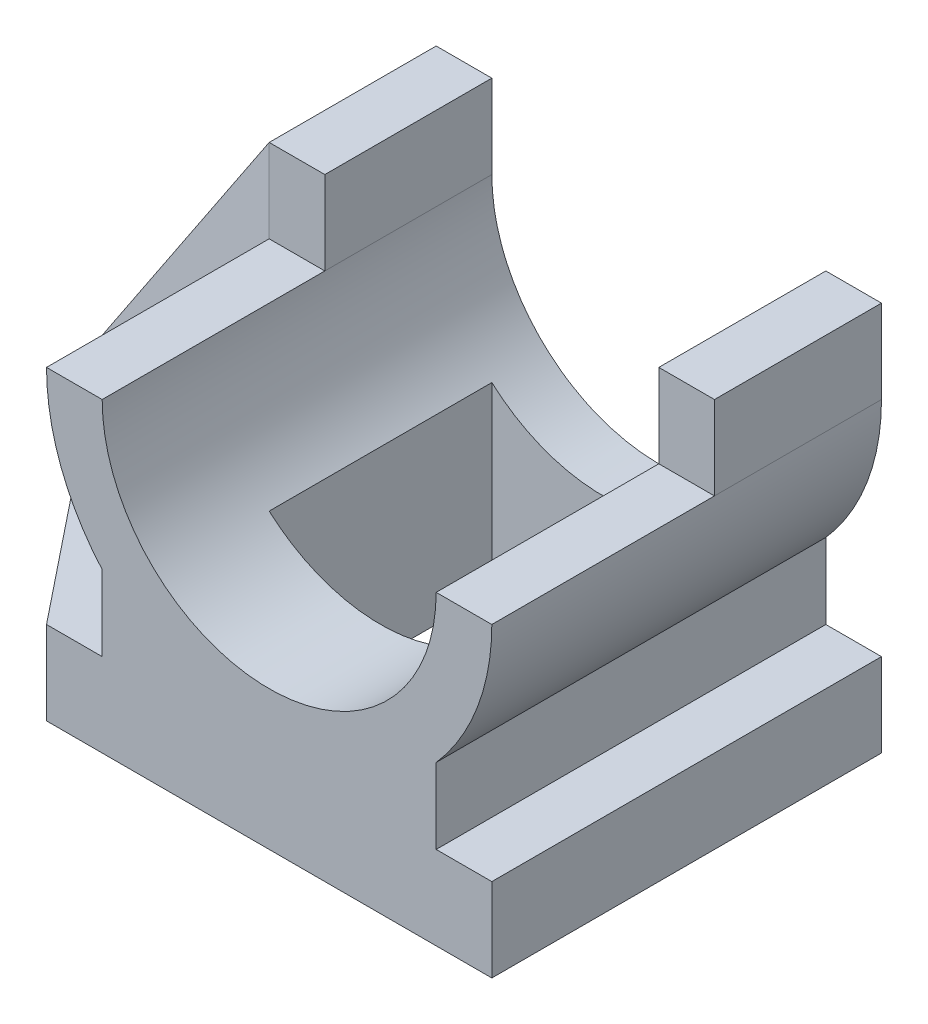
SolidWorks part; units mm, degrees
ref_plane "Front Plane" through (0, 0, 0) normal (0, 0, 1) x (1, 0, 0)
ref_plane "Top Plane" through (0, 0, 0) normal (0, 1, 0) x (1, 0, 0)
ref_plane "Right Plane" through (0, 0, 0) normal (1, 0, 0) x (0, 0, -1)
sketch "Sketch1" plane through (0, 0, 0) normal (0, 1, 0) x (1, 0, 0)
  line L0 (0, 0) -> (0, -20)
  line L1 (0, -20) -> (40, -70)
  line L2 (40, -70) -> (120, -70)
  line L3 (120, -70) -> (120, 0)
  line L4 (120, 0) -> (0, 0)
  dimension "D1" = 120
  dimension "D2" = 70
  dimension "D3" = 20
  dimension "D4" = 80
extrude "Boss-Extrude1" add sketch "Sketch1" along normal blind 15
ref_plane "Plane1" through (80, 0, 0) normal (1, 0, 0) x (0, 0, -1)
sketch "Sketch2" plane through (0, 0, 0) normal (0, 0, 1) x (1, 0, 0)
  line L0 (80, 15) -> (80, 70) construction
  line L1 (50, 15) -> (110, 15)
  line L2 (110, 15) -> (110, 28.5425)
  line L3 (120, 55) -> (40, 55)
  line L4 (50, 28.5425) -> (50, 15)
  arc A0 (110, 28.5425) -> (120, 55) centre (80, 55) ccw
  arc A1 (40, 55) -> (50, 28.5425) centre (80, 55) ccw
  dimension "D3" = 40
  dimension "D1" = 60
  dimension "D2" = 80
extrude "Boss-Extrude2" add sketch "Sketch2" along normal blind 70
sketch "Sketch3" plane through (0, 0, 0) normal (0, 0, 1) x (1, 0, 0)
  line L0 (110, 55) -> (120, 55)
  line L1 (120, 55) -> (120, 70)
  line L2 (120, 70) -> (110, 70)
  line L3 (110, 70) -> (110, 55)
  dimension "D1" = 10
  dimension "D2" = 15
extrude "Boss-Extrude3" add sketch "Sketch3" along normal blind 30
mirror "Mirror1" about plane through (80, 0, 0) normal (1, 0, 0) of "Boss-Extrude3"
sketch "Sketch4" plane through (0, 0, 0) normal (0, 0, 1) x (1, 0, 0)
  line L0 (50, 72) -> (50, 55)
  line L1 (110, 55) -> (110, 72)
  line L2 (110, 72) -> (50, 72)
  arc A0 (50, 55) -> (110, 55) centre (80, 55) ccw
  dimension "D1" = 30
  dimension "D2" = 60
extrude "Cut-Extrude1" cut sketch "Sketch4" against normal through all and the other way through all
sketch "Sketch5" plane through (0, 0, 0) normal (0, 1, 0) x (1, 0, 0)
  line L0 (60, -10) -> (100, -10)
  line L1 (100, -10) -> (100, -50)
  line L2 (100, -50) -> (60, -50)
  line L3 (60, -50) -> (60, -10)
  dimension "D1" = 40
  dimension "D2" = 40
extrude "Cut-Extrude2" cut sketch "Sketch5" against normal through all and the other way through all
sketch "Sketch6" plane through (0, 0, 0) normal (0, 0, 1) x (1, 0, 0)
  line L0 (0, 15) -> (40, 70)
  line L1 (40, 70) -> (50, 70)
  line L2 (50, 70) -> (50, 15)
  line L3 (50, 15) -> (0, 15)
  dimension "D1" = 10
  dimension "D2" = 55
  dimension "D3" = 50
extrude "Boss-Extrude4" add sketch "Sketch6" along normal blind 30
sketch "Sketch7" plane through (0, 0, 0) normal (0, 1, 0) x (1, 0, 0)
  line L0 (0, -20) -> (40, -30)
  line L1 (40, -30) -> (0, -30)
  line L2 (0, -30) -> (0, -20)
  dimension "D1" = 40
  dimension "D2" = 10
extrude "Cut-Extrude3" cut sketch "Sketch7" along normal blind 60 from offset 15
